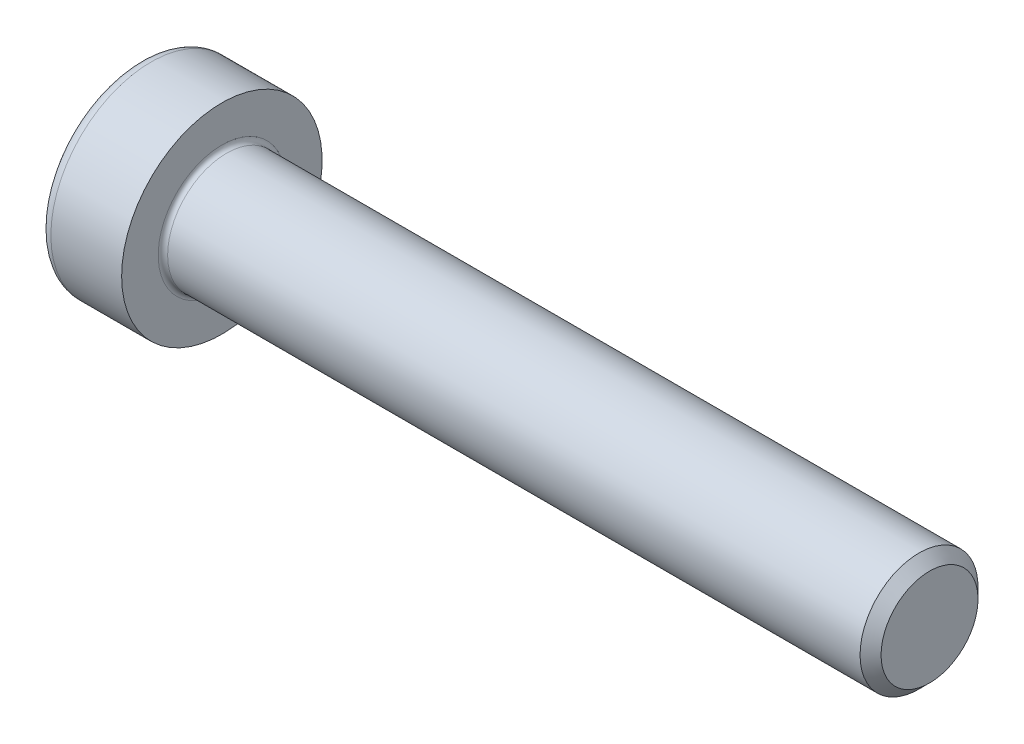
SolidWorks part; units mm, degrees
revolve "Base-Revolve" add sketch "BodySke"
sketch "BodySke" plane through (0, 0, 0) normal (0, 0, 1) x (1, 0, 0)
  line L0 (0, 0) -> (0, 4.25)
  line L1 (0, 4.25) -> (3.5, 4.25)
  line L2 (3.5, 4.25) -> (3.5, 2.5)
  line L3 (3.5, 2.5) -> (33.055, 2.5)
  line L4 (33.5, 2.055) -> (33.5, 0)
  line L5 (33.5, 0) -> (0, 0)
  line L6 (-31.75, 0) -> (127, 0) construction
  line L8 (33.5, 2.055) -> (33.055, 2.5)
  line L10 (33.5, -2.055) -> (33.055, -2.5) construction
  line L11 (4.3, 4.525) -> (4.3, -1.825) construction
  line L12 (17.5, 4.525) -> (17.5, -1.825) construction
  line L13 (-26.5, 4.525) -> (-26.5, -1.825) construction
  dimension "Body_ch_ang" = 45
  dimension "Thread_length" = 60
cosmetic thread "ThreadCosmetic"
fillet "Fillet1" radius 0.2 1 edges at (3.5, 0, 2.5)
fillet "Fillet2" radius 0.5 1 edges at (0, 0, 4.25)
ref_plane "Plane1" through (0, 0, 0) normal (0, 0, 1) x (1, 0, 0)
ref_plane "Plane2" through (0, 0, 0) normal (0, 1, 0) x (1, 0, 0)
ref_plane "Plane3" through (0, 0, 0) normal (1, 0, 0) x (0, 0, -1)
sketch "HexSke" plane through (0, 0, 0) normal (-1, 0, 0) x (0, 0.5, 0.866)
  line L0 (1.1547, 2) -> (-1.1547, 2)
  line L1 (-1.1547, 2) -> (-2.3094, 0)
  line L2 (1.1547, 2) -> (2.3094, 0)
  line L3 (1.1547, -2) -> (2.3094, 0)
  line L4 (1.1547, -2) -> (-1.1547, -2)
  line L5 (-1.1547, -2) -> (-2.3094, 0)
extrude "Hex" cut sketch "HexSke" against normal blind 2
sketch "PilotSke" plane through (0, 0, 0) normal (0, 0, 1) x (1, 0, 0)
  line L0 (0, 2) -> (2, 2)
  line L1 (2, 2) -> (2.433, 1.25)
  line L2 (-31.75, 0) -> (127, 0) construction
  line L3 (4.7217, 0) -> (0, 0)
  line L4 (0, 0) -> (0, 2)
  line L5 (2.433, 1.25) -> (4, 1.25)
  line L6 (0, 0) -> (47.625, 0) construction
  line L7 (4, 1.25) -> (4.7217, 0)
  dimension "D2" = 60
  dimension "Pilot_dia" = 2.5
revolve "Hex-PreBroach" cut sketch "PilotSke" angle 360 about L6
sketch "ThdSchSke" plane through (0, 0, 0) normal (0, 0, 1) x (1, 0, 0)
  line L0 (17.5, -2.055) -> (17.1884, -2.5)
  line L1 (17.5, -2.055) -> (17.8116, -2.5)
  line L2 (17.8116, -2.5) -> (17.8116, -3.125)
  line L3 (-3.175, 0) -> (5.1513, 0) construction
  line L4 (0, 3.75) -> (0, -3.75) construction
  line L5 (17.8116, -3.125) -> (17.1884, -3.125)
  line L6 (17.1884, -3.125) -> (17.1884, -2.5)
revolve "ThreadSchematic" [suppressed] cut sketch "ThdSchSke" angle 360 about L3
pattern_linear "ThdSchPat" [suppressed]
equation "\"D2@HexSke\" = \"Hex_size@HexSke\" / 2"
equation "\"D1@HexSke\" = \"Hex_size@HexSke\" / 2"
equation "\"D1@PilotSke\" = \"Hex_size@HexSke\" / 2"
equation "\"Thread_minor@ThreadCosmetic\"  =  \"Minor_dia@BodySke\""
equation "\"Depth@PilotSke\" =  \"Key_eng@Hex\""
equation "\"Thread_length@ThreadCosmetic\" = ((sgn( (\"Length@BodySke\" - \"Advance@BodySke\" * 3.0) - \"Thread_nom@BodySke\" )-1)*( (\"Length@BodySke\" - \"Advance@BodySke\" * 3.0) - \"Thread_nom@BodySke\" ))/-2+ \"Thread_nom@BodySke\""
equation "\"Thread_minor@ThdSchSke\" = \"Minor_dia@BodySke\""
equation "\"Diameter@ThdSchSke\" = \"Diameter@BodySke\""
equation "\"Overcut@ThdSchSke\" = \"Diameter@BodySke\" * 1.25"
equation "\"Start@ThdSchSke\" = \"Head_ht@BodySke\" + \"Length@BodySke\" - \"Thread_length@ThreadCosmetic\"  '---Non-countersunk---"
equation "\"Num_threads@ThdSchPat\" = int( \"Thread_length@ThreadCosmetic\" / \"Advance@BodySke\" + 0.999 )  + 1"
equation "\"Advance@ThdSchPat\" = \"Thread_length@ThreadCosmetic\" /  (\"Num_threads@ThdSchPat\" - 1) 'relax it"
equation "\"Num_threads@ThdSchPat\" = \"Num_threads@ThdSchPat\" - sgn( \"Num_threads@ThdSchPat\" - 1) '---chamfered tips only---"
